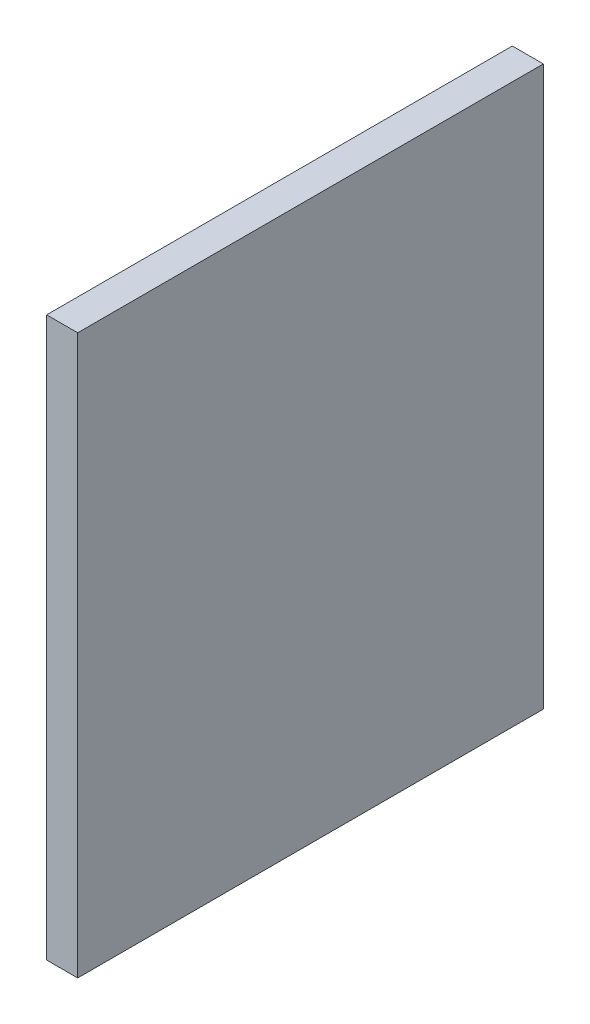
SolidWorks part; units mm, degrees
ref_plane "Front Plane" through (0, 0, 0) normal (0, 0, 1) x (1, 0, 0)
ref_plane "Top Plane" through (0, 0, 0) normal (0, 1, 0) x (1, 0, 0)
ref_plane "Right Plane" through (0, 0, 0) normal (1, 0, 0) x (0, 0, -1)
sketch "Sketch1" plane through (0, 0, 0) normal (1, 0, 0) x (0, 0, -1)
  line L1 (15, -18) -> (-15, -18)
  line L2 (15, -18) -> (15, 18)
  line L3 (15, 18) -> (-15, 18)
  line L4 (-15, -18) -> (-15, 18)
  line L5 (15, -18) -> (-15, 18) construction
  line L6 (15, 18) -> (-15, -18) construction
  point P0 (0, 0)
  dimension "D1" = 30
  dimension "D2" = 36
extrude "Boss-Extrude1" add sketch "Sketch1" along normal blind 2
